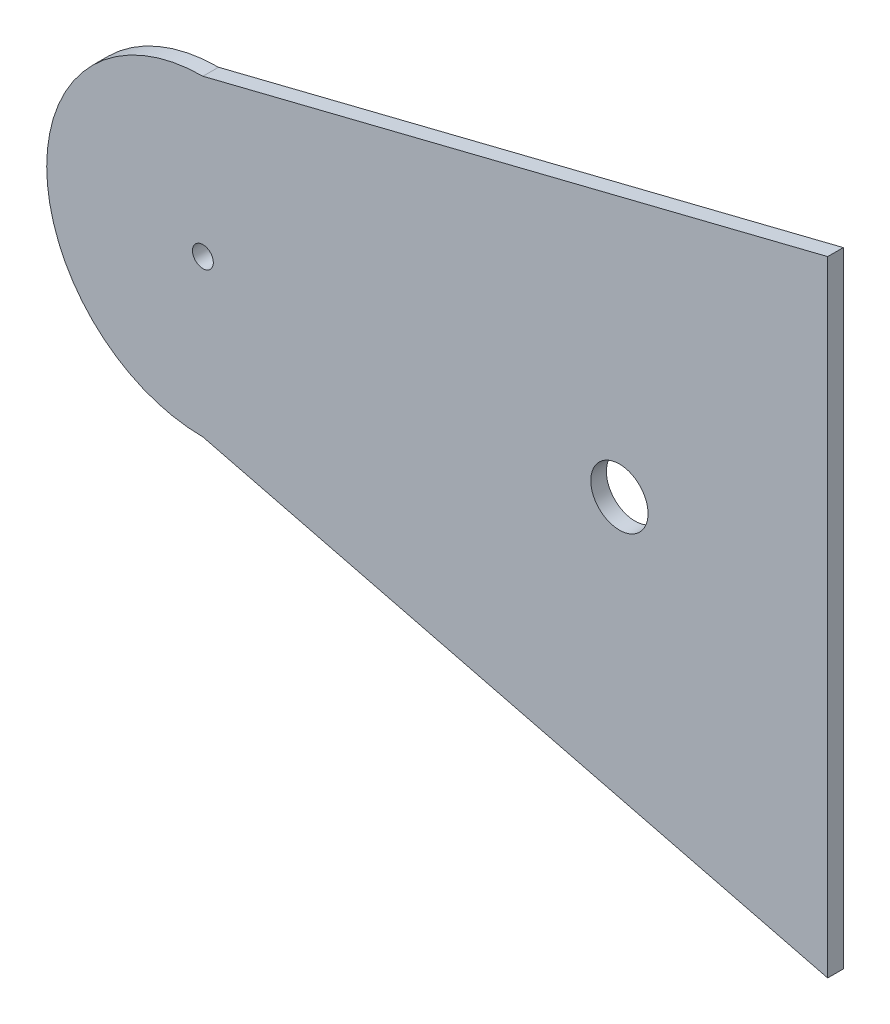
SolidWorks part; units mm, degrees
ref_plane "前视基准面" through (0, 0, 0) normal (0, 0, 1) x (1, 0, 0)
ref_plane "上视基准面" through (0, 0, 0) normal (0, 1, 0) x (1, 0, 0)
ref_plane "右视基准面" through (0, 0, 0) normal (1, 0, 0) x (0, 0, -1)
sketch "草图1" plane through (0, 0, 0) normal (0, 0, 1) x (1, 0, 0)
  line L261 (174.0026, 13.7079) -> (254.0026, 13.7079) construction
  line L264 (174.0026, 43.7079) -> (294.0026, 73.7079)
  line L272 (294.0026, 13.7079) -> (294.0026, 73.7079)
  line L274 (294.0026, 13.7079) -> (294.0026, -46.2921)
  line L276 (174.0026, -16.2921) -> (294.0026, -46.2921)
  line L277 (254.0026, 13.7079) -> (294.0026, 13.7079) construction
  circle A37 centre (174.0026, 13.7079) radius 2
  circle A38 centre (254.0026, 13.7079) radius 5.5
  circle A40 centre (174.0026, 13.7079) radius 30 construction
  arc A41 (174.0026, -16.2921) -> (174.0026, 43.7079) centre (174.0026, 13.7079) cw
extrude "凸台-拉伸1" add sketch "草图1" along normal blind 3
